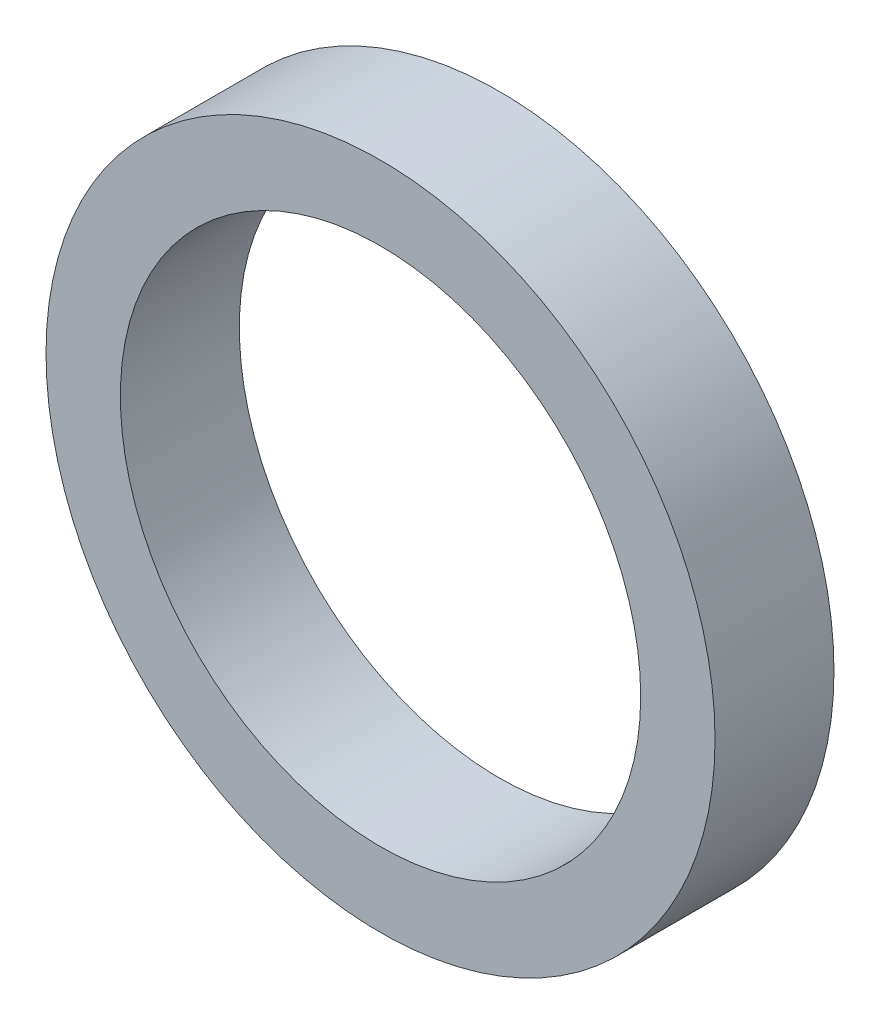
SolidWorks part; units mm, degrees
material "AISI 304"
ref_plane "Front" through (0, 0, 0) normal (0, 0, 1) x (1, 0, 0)
ref_plane "Top" through (0, 0, 0) normal (0, 1, 0) x (1, 0, 0)
ref_plane "Right" through (0, 0, 0) normal (1, 0, 0) x (0, 0, -1)
sketch "Sketch1" plane through (0, 0, 0) normal (0, 0, 1) x (1, 0, 0)
  circle A0 centre (0, 0) radius 7.1437
  circle A1 centre (0, 0) radius 5.5562
  dimension "D1" = 14.2875
  dimension "D2" = 11.1125
extrude "Boss-Extrude1" add sketch "Sketch1" along normal mid plane 2.54
ref_plane "Plane1" through (0, 7.112, 0) normal (0, 1, 0) x (1, 0, 0)
sketch "Sketch2" plane through (0, 7.112, 0) normal (0, 1, 0) x (1, 0, 0)
  point P0 (0, 0)
